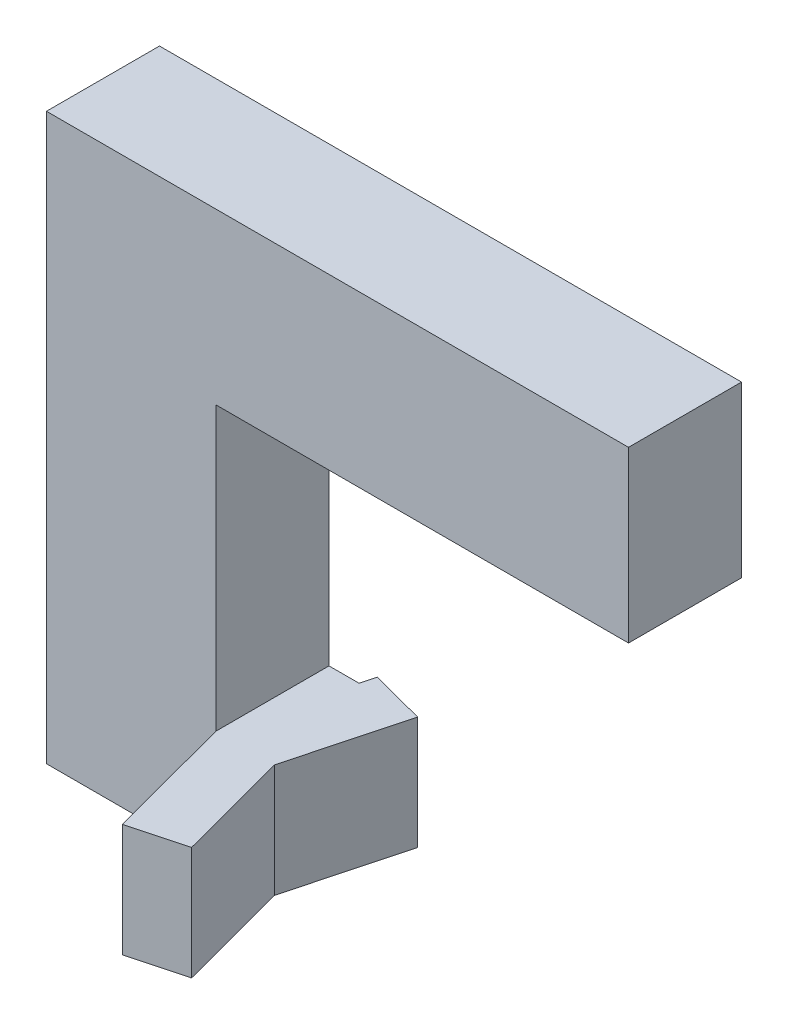
SolidWorks part; units mm, degrees
ref_plane "Front Plane" through (0, 0, 0) normal (0, 0, 1) x (1, 0, 0)
ref_plane "Top Plane" through (0, 0, 0) normal (0, 1, 0) x (1, 0, 0)
ref_plane "Right Plane" through (0, 0, 0) normal (1, 0, 0) x (0, 0, -1)
sketch "Sketch1" plane through (0, 0, 0) normal (0, 0, 1) x (1, 0, 0)
  line L0 (51.5, 0) -> (0, 0)
  line L1 (0, 0) -> (0, -50)
  line L2 (0, -50) -> (15, -50)
  line L3 (15, -50) -> (15, -15)
  line L4 (15, -15) -> (51.5, -15)
  line L5 (51.5, -15) -> (51.5, 0)
  dimension "D1" = 51.5
  dimension "D2" = 50
  dimension "D3" = 15
  dimension "D4" = 15
extrude "Boss-Extrude1" add sketch "Sketch1" along normal mid plane 10
sketch "Sketch2" plane through (0, -50, 0) normal (0, -1, 0) x (1, 0, 0)
  line L0 (18, -6.2846) -> (15, 5)
  line L1 (15, 5) -> (18, 16.2846)
  line L3 (15, 5) -> (25.3473, 5) construction
  line L4 (15, 5) -> (51.5, 5) construction
  line L5 (18, 16.2846) -> (22.8322, 15)
  line L6 (22.8322, 15) -> (20.1737, 5)
  line L7 (20.1737, 5) -> (22.8322, -5)
  line L8 (22.8322, -5) -> (18, -6.2846)
  line L9 (15, -5) -> (17.6585, -5)
  line L10 (15, -5) -> (51.5, -5) construction
  point P3 (25.3604, -33.2468)
  point P11 (30.2595, 36.4145)
  point P12 (25.0796, 16.7046)
  point P18 (20.2691, 21.5443)
  point P19 (22.892, -8.1617)
  line M9 (15, -5) -> (15, 5)
  dimension "D1" = 5
  dimension "D2" = 3
extrude "Boss-Extrude2" add sketch "Sketch2" against normal blind 10 contours L8 L7 L6 L5 L1 L0 | L9 L0 M9 | L1 L3 L6 L5
